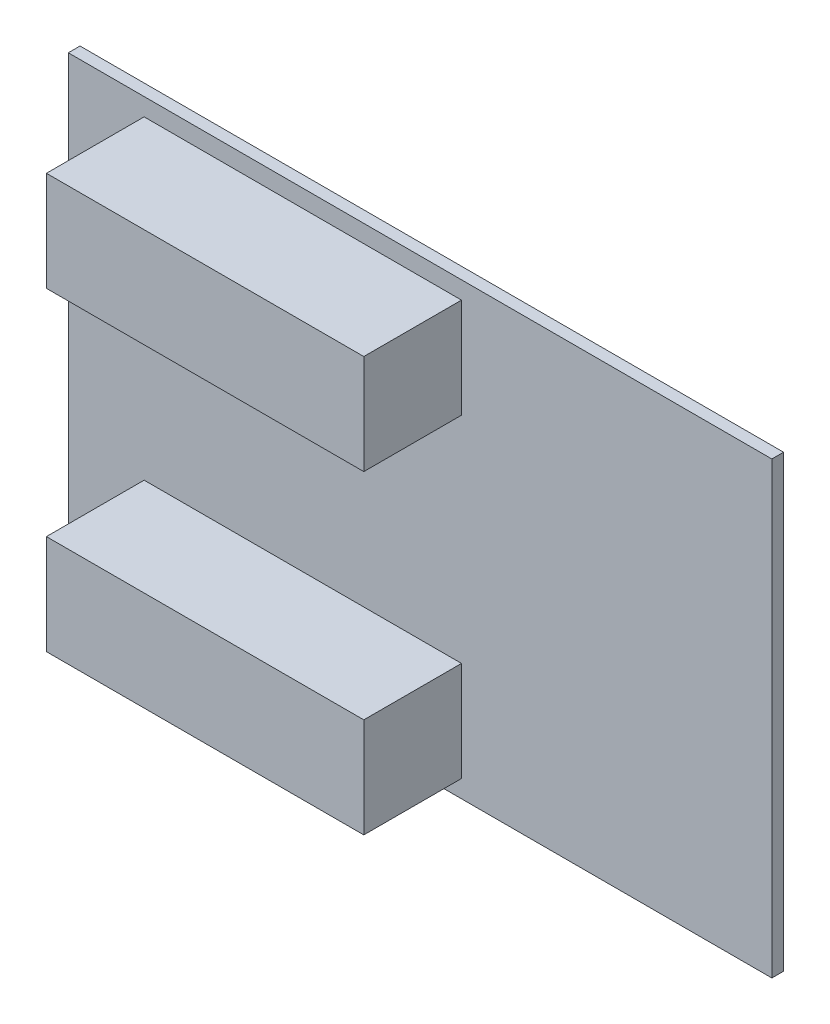
SolidWorks part; units mm, degrees
ref_plane "前视基准面" through (0, 0, 0) normal (0, 0, 1) x (1, 0, 0)
ref_plane "上视基准面" through (0, 0, 0) normal (0, 1, 0) x (1, 0, 0)
ref_plane "右视基准面" through (0, 0, 0) normal (1, 0, 0) x (0, 0, -1)
sketch "草图1" plane through (0, 0, 0) normal (0, 0, 1) x (1, 0, 0)
  line L1 (-90, 57.5) -> (90, 57.5)
  line L2 (-90, 57.5) -> (-90, -57.5)
  line L3 (-90, -57.5) -> (90, -57.5)
  line L4 (90, 57.5) -> (90, -57.5)
  line L5 (-90, 57.5) -> (90, -57.5) construction
  line L6 (-90, -57.5) -> (90, 57.5) construction
  point P0 (0, 0)
  dimension "D1" = 115
  dimension "D2" = 180
extrude "凸台-拉伸1" add sketch "草图1" along normal blind 3
sketch "草图7" plane through (0, 0, 0) normal (0, 0, -1) x (-1, 0, 0)
  line L0 (-90, 57.5) -> (90, 57.5) construction
  line L1 (-8.1, 50.5) -> (68.1, 50.5)
  line L2 (-8.1, 50.5) -> (-8.1, 30)
  line L3 (-8.1, 30) -> (68.1, 30)
  line L4 (68.1, 50.5) -> (68.1, 30)
  line L5 (90, 57.5) -> (90, -57.5) construction
  dimension "D1" = 20.5
  dimension "D2" = 76.2
  dimension "D3" = 7
  dimension "D4" = 21.9
extrude "电池位切除-拉伸3" cut sketch "草图7" against normal up to next
sketch "草图8" plane through (0, 0, 3) normal (0, 0, 1) x (1, 0, 0)
  line L12 (8.1, 50.5) -> (8.1, 30) construction
  line L13 (-70.6, 53) -> (10.6, 53)
  line L14 (-70.6, 53) -> (-70.6, 27.5)
  line L15 (-70.6, 27.5) -> (10.6, 27.5)
  line L16 (10.6, 53) -> (10.6, 27.5)
  line L17 (-68.1, 30) -> (-68.1, 50.5) construction
  line L18 (-68.1, 50.5) -> (8.1, 50.5) construction
  line L19 (8.1, 30) -> (-68.1, 30) construction
  line L20 (-68.1, 50.5) -> (8.1, 50.5)
  line L21 (8.1, 30) -> (-68.1, 30)
  line L22 (8.1, 50.5) -> (8.1, 30)
  line L23 (-68.1, 30) -> (-68.1, 50.5) construction
  line L24 (-68.1, 30) -> (-68.1, 50.5)
  dimension "D1" = 2.5
  dimension "D2" = 2.5
  dimension "D3" = 2.5
  dimension "D4" = 2.5
extrude "凸台-拉伸2" add sketch "草图8" along normal blind 25
sketch "草图9" plane through (0, 0, 28) normal (0, 0, 1) x (1, 0, 0)
  line L0 (10.6, 53) -> (-70.6, 53) construction
  line L5 (10.6, 53) -> (-70.6, 53)
  line L6 (-70.6, 27.5) -> (10.6, 27.5) construction
  line L7 (-70.6, 27.5) -> (10.6, 27.5)
  line L8 (10.6, 27.5) -> (10.6, 53) construction
  line L9 (10.6, 27.5) -> (10.6, 53)
  line L10 (-70.6, 53) -> (-70.6, 27.5) construction
  line L11 (-70.6, 53) -> (-70.6, 27.5)
extrude "凸台-拉伸3" add sketch "草图9" against normal blind 2.5
sketch "草图4" plane through (0, 0, 0) normal (0, 0, -1) x (-1, 0, 0)
  line L0 (68.1, 30) -> (68.1, 50.5) construction
  line L5 (68.1, 40.25) -> (84.6307, 40.25) construction
  line L10 (83.2374, -53.4277) -> (79.3374, -53.4277) construction
  line L11 (83.2374, -49.6277) -> (83.2374, -53.4277) construction
  line L12 (79.3374, -49.6277) -> (83.2374, -49.6277) construction
  line L29 (68.1, 36.25) -> (72.1, 36.25)
  line L30 (72.1, 36.25) -> (72.1, 44.25)
  line L31 (72.1, 44.25) -> (68.1, 44.25)
  line L32 (68.1, 44.25) -> (68.1, 36.25)
  dimension "D1" = 8
  dimension "D2" = 4
extrude "切除-拉伸2" cut sketch "草图4" along normal blind 1.6 from surface at -3 starting at face at (0, 0, 3)
mirror "镜向1" about plane through (0, 0, 0) normal (0, 1, 0) of "切除-拉伸2", "凸台-拉伸3", "凸台-拉伸2", "电池位切除-拉伸3"
